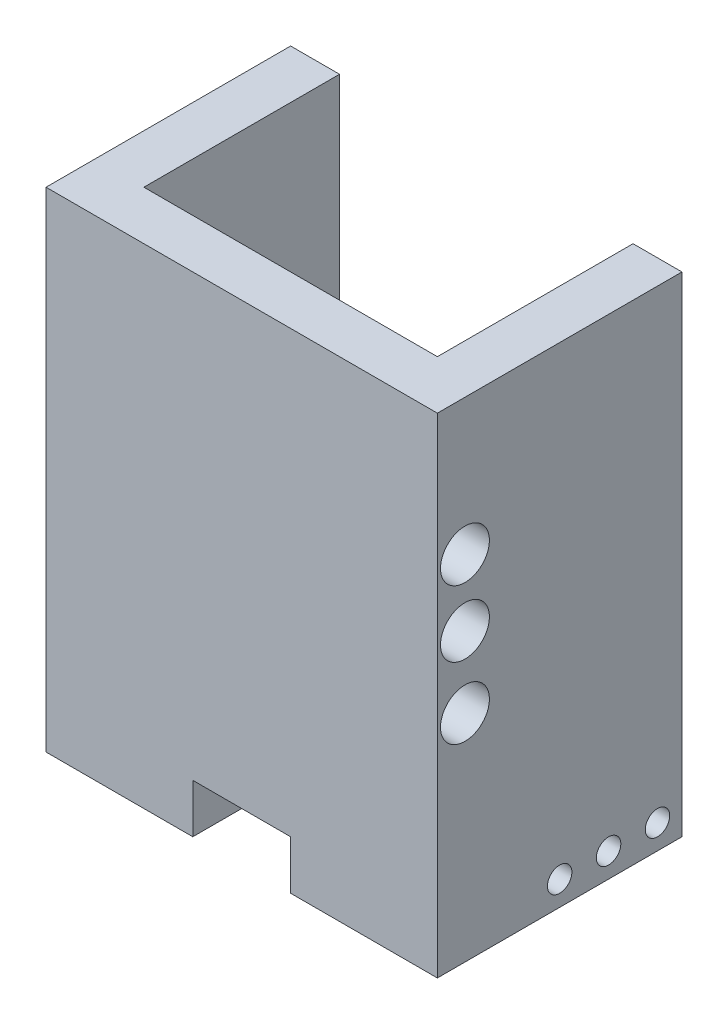
SolidWorks part; units mm, degrees
material "1060 Alloy"
ref_plane "Front Plane" through (0, 0, 0) normal (0, 0, 1) x (1, 0, 0)
ref_plane "Top Plane" through (0, 0, 0) normal (0, 1, 0) x (1, 0, 0)
ref_plane "Right Plane" through (0, 0, 0) normal (1, 0, 0) x (0, 0, -1)
sketch "Sketch1" plane through (0, 0, 0) normal (0, 0, 1) x (1, 0, 0)
  line L0 (12.7, -127) -> (50.8, -127)
  line L1 (-50.8, -127) -> (-12.7, -127)
  line L2 (-50.8, -127) -> (-50.8, 0)
  line L3 (-50.8, 0) -> (50.8, 0)
  line L4 (50.8, -127) -> (50.8, 0)
  line L6 (-12.7, -127) -> (-12.7, -114.3)
  line L7 (-12.7, -114.3) -> (12.7, -114.3)
  line L8 (12.7, -127) -> (12.7, -114.3)
  dimension "D1" = 101.6
  dimension "D2" = 127
  dimension "D3" = 12.7
  dimension "D4" = 25.4
  dimension "D5" = 38.1
extrude "Boss-Extrude1" add sketch "Sketch1" against normal blind 63.5
sketch "Sketch2" plane through (0, 0, 0) normal (0, 1, 0) x (1, 0, 0)
  line L4 (-38.1, 50.8) -> (-38.1, 63.5)
  line L5 (50.8, 63.5) -> (-50.8, 63.5) construction
  line L6 (-38.1, 63.5) -> (38.1, 63.5)
  line L7 (38.1, 63.5) -> (38.1, 50.8)
  line L8 (-38.1, 12.7) -> (38.1, 12.7)
  line L9 (38.1, 12.7) -> (38.1, 50.8)
  line L10 (38.1, 50.8) -> (-38.1, 50.8)
  line L11 (-38.1, 50.8) -> (-38.1, 12.7)
  line L12 (-38.1, 12.7) -> (38.1, 12.7)
  line L13 (38.1, 12.7) -> (38.1, 50.8)
  line L15 (-38.1, 50.8) -> (-38.1, 12.7)
  dimension "D1" = 12.7
extrude "Cut-Extrude1" cut sketch "Sketch2" against normal through all
sketch "Sketch3" plane through (-50.8, 0, 0) normal (-1, 0, 0) x (0, 0, 1)
  line L0 (0, 0) -> (0, -127) construction
  line L1 (0, -25.4) -> (-14.2718, -25.4)
  line L2 (0, -25.4) -> (0, -82.296)
  line L3 (0, -82.296) -> (-14.2718, -82.296)
  line L4 (-14.2718, -25.4) -> (-14.2718, -82.296)
  line L5 (-63.5, 0) -> (0, 0) construction
  circle A0 centre (-7.1598, -35.3228) radius 6.35
  circle A1 centre (-7.1598, -52.5302) radius 6.35
  circle A2 centre (-7.1598, -71.0283) radius 6.35
  dimension "D3" = 12.7
  dimension "D1" = 56.896
  dimension "D2" = 25.4
  dimension "D4" = 14.2718
  dimension "D5" = 7.112
extrude "Cut-Extrude2" cut sketch "Sketch3" against normal through all contours A0 | A1 | A2
sketch "Sketch4" plane through (-50.8, 0, 0) normal (-1, 0, 0) x (0, 0, 1)
  line L0 (-63.5, 0) -> (-63.5, -127) construction
  line L1 (-63.5, -127) -> (0, -127) construction
  circle A0 centre (-57.15, -120.65) radius 3.175
  circle A1 centre (-44.45, -120.65) radius 3.175
  circle A2 centre (-31.75, -120.65) radius 3.175
  dimension "D1" = 6.35
  dimension "D2" = 6.35
  dimension "D3" = 6.35
  dimension "D4" = 3
extrude "Cut-Extrude3" cut sketch "Sketch4" against normal through all
